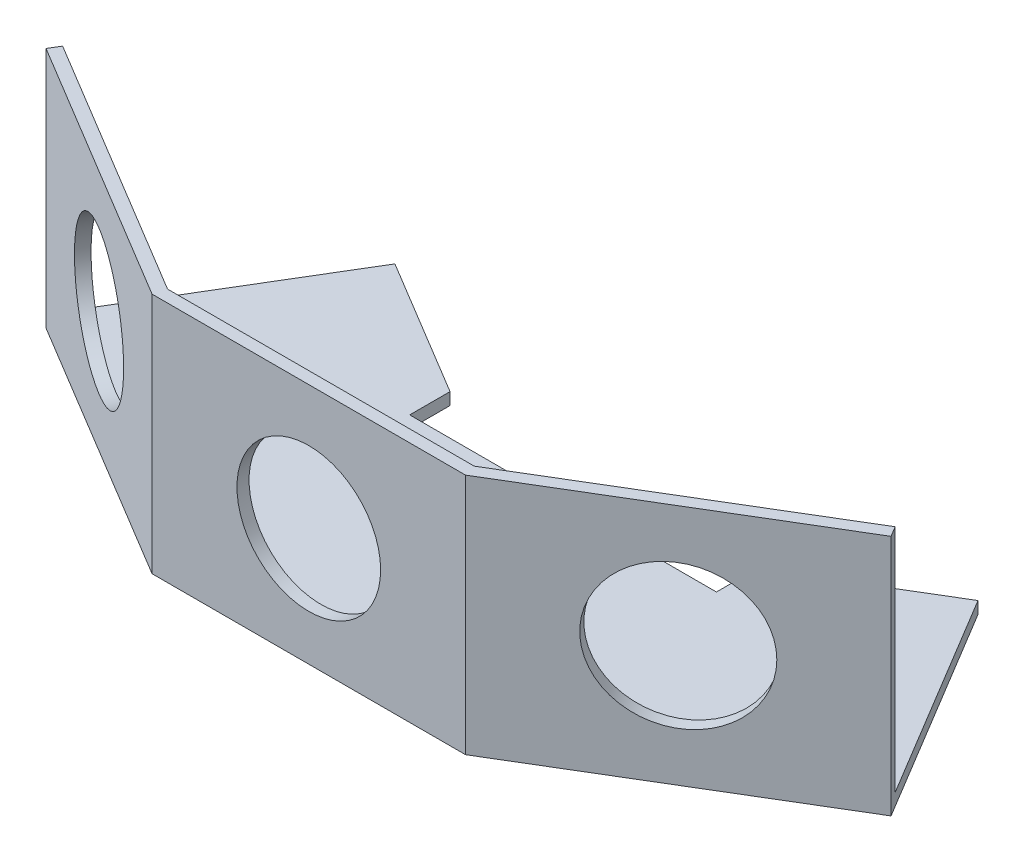
SolidWorks part; units mm, degrees
ref_plane "Alzado" through (0, 0, 0) normal (0, 0, 1) x (1, 0, 0)
ref_plane "Planta" through (0, 0, 0) normal (0, 1, 0) x (1, 0, 0)
ref_plane "Vista lateral" through (0, 0, 0) normal (1, 0, 0) x (0, 0, -1)
sketch "Croquis1" plane through (0, 0, 0) normal (0, 1, 0) x (1, 0, 0)
  line L0 (-19, -15) -> (-51.5714, 4.573)
  line L1 (19, -15) -> (-19, -15)
  line L2 (19, 15) -> (-19, 15)
  line L3 (19, -15) -> (-19, 15) construction
  line L4 (19, 15) -> (-19, -15) construction
  line L5 (-51.5714, 4.573) -> (-36.1191, 30.2873)
  line L6 (-36.1191, 30.2873) -> (-19, 20)
  line L7 (-19, 20) -> (-19, 15)
  line L8 (0, 16.7969) -> (0, -21.637) construction
  line L9 (19, -15) -> (51.5714, 4.573)
  line L10 (51.5714, 4.573) -> (36.1191, 30.2873)
  line L11 (19, 20) -> (19, 15)
  line L12 (36.1191, 30.2873) -> (19, 20)
  point P0 (0, 0)
  point P14 (0, 0)
  dimension "D1" = 30
  dimension "D2" = 38
  dimension "D3" = 38
  dimension "D4" = 30
  dimension "D5" = 35
extrude "Saliente-Extruir1" add sketch "Croquis1" along normal blind 1.5
sketch "Croquis2" plane through (0, 0, 0) normal (0, 1, 0) x (1, 0, 0)
  line L3 (-51.5714, 4.573) -> (-52.344, 3.2873)
  line L4 (52.344, 3.2873) -> (51.5714, 4.573)
  line L5 (-51.5714, 4.573) -> (-19, -15)
  line L6 (19.416, -16.5) -> (52.344, 3.2873)
  line L7 (-19.416, -16.5) -> (19.416, -16.5)
  line L8 (-52.344, 3.2873) -> (-19.416, -16.5)
  line L9 (19.416, -16.5) -> (52.344, 3.2873)
  line L10 (-19.416, -16.5) -> (19.416, -16.5)
  line L11 (-52.344, 3.2873) -> (-19.416, -16.5)
  line L12 (-19, -15) -> (19, -15)
  line L13 (19, -15) -> (51.5714, 4.573)
  dimension "D1" = 1.5
extrude "Saliente-Extruir2" add sketch "Croquis2" along normal blind 30
sketch "Croquis3" plane through (0, 0, 16.5) normal (0, 0, 1) x (1, 0, 0)
  circle A0 centre (0, 14.5639) radius 8.9
  point P2 (0, 0)
  point P4 (0, 0)
  point P7 (0, 0)
  dimension "D1" = 17.8
extrude "Cortar-Extruir1" cut sketch "Croquis3" against normal blind 30
sketch "Croquis4" plane through (12.4359, 0, 20.6945) normal (0.5151, 0, 0.8571) x (0.8571, 0, -0.5151)
  line L0 (8.1435, 30) -> (46.5595, 30) construction
  line L1 (46.5595, 30) -> (46.5595, 0) construction
  circle A0 centre (27.3515, 15) radius 8.9
  point P2 (0, 0)
  point P7 (27.3515, 30)
  point P10 (46.5595, 15)
  dimension "D1" = 17.8
extrude "Cortar-Extruir2" cut sketch "Croquis4" against normal blind 30
sketch "Croquis5" plane through (-12.4359, 0, 20.6945) normal (-0.5151, 0, 0.8571) x (0.8571, 0, 0.5151)
  line L0 (-46.5595, 30) -> (-8.1435, 30) construction
  line L1 (-46.5595, 30) -> (-46.5595, 0) construction
  circle A0 centre (-27.3515, 15) radius 8.9
  point P2 (0, 0)
  point P5 (-27.3515, 30)
  point P6 (0, 0)
  point P9 (-46.5595, 15)
  dimension "D1" = 17.8
extrude "Cortar-Extruir3" cut sketch "Croquis5" against normal blind 30
